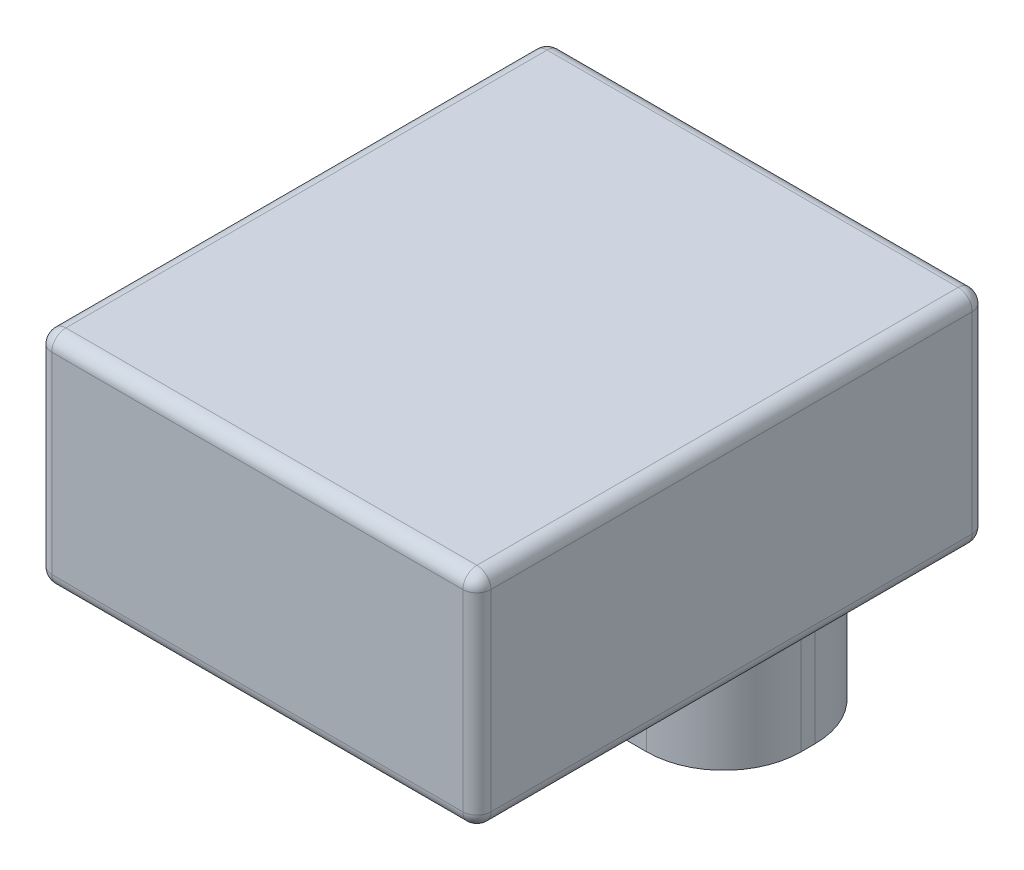
SolidWorks part; units mm, degrees
material "Custom Plastic"
ref_plane "X-Y Datum" through (0, 0, 0) normal (0, 0, 1) x (1, 0, 0)
ref_plane "X-Z Datum" through (0, 0, 0) normal (0, 1, 0) x (1, 0, 0)
ref_plane "Y-Z Datum" through (0, 0, 0) normal (1, 0, 0) x (0, 0, -1)
sketch "Sketch1" plane through (0, 0, 0) normal (0, 1, 0) x (1, 0, 0)
  line L1 (-31.3, 36.3) -> (31.3, 36.3)
  line L2 (-31.3, 36.3) -> (-31.3, -36.3)
  line L3 (-31.3, -36.3) -> (31.3, -36.3)
  line L4 (31.3, 36.3) -> (31.3, -36.3)
  line L5 (-31.3, 36.3) -> (31.3, -36.3) construction
  line L6 (-31.3, -36.3) -> (31.3, 36.3) construction
  point P0 (0, 0)
  dimension "D1" = 62.6
  dimension "D2" = 72.6
extrude "Boss-Extrude1" add sketch "Sketch1" along normal blind 24.14
sketch "Sketch2" plane through (0, 0, 0) normal (0, -1, 0) x (1, 0, 0)
  line L0 (25, -17.2) -> (-25, -17.2) construction
  line L6 (-25, -5.2) -> (25, -5.2)
  line L7 (-25, -5.2) -> (-25, -29.2)
  line L8 (-25, -29.2) -> (25, -29.2)
  line L9 (25, -5.2) -> (25, -29.2)
  line L11 (-31.3, 36.3) -> (31.3, 36.3) construction
  point P4 (0, -17.2)
  dimension "D1" = 65.5
  dimension "D2" = 24
  dimension "D3" = 50
extrude "Boss-Extrude2" add sketch "Sketch2" along normal blind 19
sketch "Sketch3" plane through (0, 24.14, 0) normal (0, 1, 0) x (1, 0, 0)
  line L4 (31.3, -36.3) -> (31.3, 36.3)
  line L5 (31.3, 36.3) -> (-31.3, 36.3)
  line L6 (-31.3, 36.3) -> (-31.3, -36.3)
  line L7 (-31.3, -36.3) -> (31.3, -36.3)
  line L8 (31.3, -36.3) -> (31.3, 36.3)
  line L9 (31.3, 36.3) -> (-31.3, 36.3)
  line L10 (-31.3, 36.3) -> (-31.3, -36.3)
  line L11 (-31.3, -36.3) -> (31.3, -36.3)
  dimension "D1" = 0
extrude "Boss-Extrude3" add sketch "Sketch3" along normal blind 7.3
fillet "Fillet1" radius 2 12 edges at (0, 0, -36.3) (0, 0, 36.3) (-31.3, 15.72, -36.3) (-31.3, 15.72, 36.3) (-31.3, 0, 0) (31.3, 15.72, 36.3) (31.3, 15.72, -36.3) (31.3, 0, 0) (0, 31.44, -36.3) (0, 31.44, 36.3) (-31.3, 31.44, 0) (31.3, 31.44, 0)
fillet "Fillet2" radius 11 4 edges at (25, -9.5, -5.2) (25, -9.5, -29.2) (-25, -9.5, -29.2) (-25, -9.5, -5.2)
